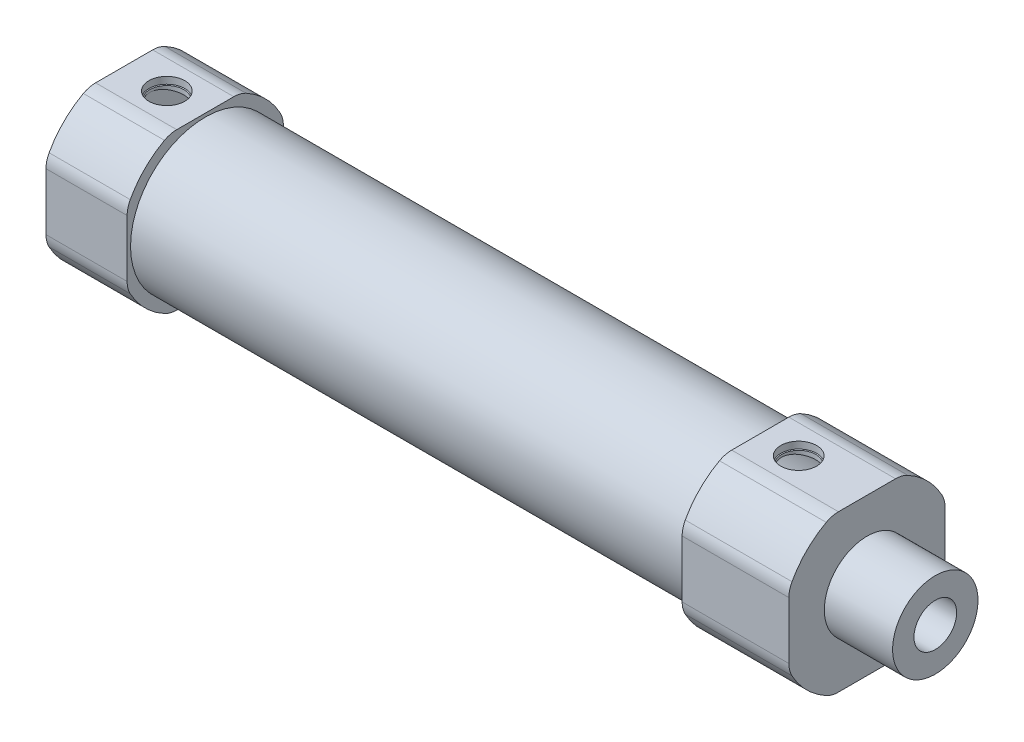
SolidWorks part; units mm, degrees
material "6061-T6 (SS)"
ref_plane "前视基准面" through (0, 0, 0) normal (0, 0, 1) x (1, 0, 0)
ref_plane "上视基准面" through (0, 0, 0) normal (0, 1, 0) x (1, 0, 0)
ref_plane "右视基准面" through (0, 0, 0) normal (1, 0, 0) x (0, 0, -1)
sketch "主筒" plane through (0, 0, 0) normal (1, 0, 0) x (0, 0, -1)
  circle A0 centre (0, 0) radius 8.75
  dimension "D1" = 17.5
extrude "主缸筒" add sketch "主筒" along normal blind 87
sketch "前头1" plane through (87, 0, 0) normal (1, 0, 0) x (0, 0, -1)
  line L1 (-9.15, 9.15) -> (9.15, 9.15)
  line L2 (-9.15, 9.15) -> (-9.15, -9.15)
  line L3 (-9.15, -9.15) -> (9.15, -9.15)
  line L4 (9.15, 9.15) -> (9.15, -9.15)
  line L5 (-9.15, 9.15) -> (9.15, -9.15) construction
  line L6 (-9.15, -9.15) -> (9.15, 9.15) construction
  circle A0 centre (0, 0) radius 10
  point P0 (0, 0)
  circle M3 centre (0, 0) radius 8.75
  dimension "D2" = 20
  dimension "D1" = 18.3
extrude "前头" add sketch "前头1" against normal blind 12.5 contours L2 A0 L3 M3
sketch "后头1" plane through (0, 0, 0) normal (-1, 0, 0) x (0, 0, 1)
  line L1 (-9.15, 9.15) -> (9.15, 9.15)
  line L2 (-9.15, 9.15) -> (-9.15, -9.15)
  line L3 (-9.15, -9.15) -> (9.15, -9.15)
  line L4 (9.15, 9.15) -> (9.15, -9.15)
  line L5 (-9.15, 9.15) -> (9.15, -9.15) construction
  line L6 (-9.15, -9.15) -> (9.15, 9.15) construction
  circle A0 centre (0, 0) radius 10
  point P0 (0, 0)
  circle M9 centre (0, 0) radius 8.75
  dimension "D2" = 20
  dimension "D1" = 18.3
extrude "后头" add sketch "后头1" against normal blind 9.5 contours L4 A0 L1 L2 L3 M9
sketch "气管接头1" plane through (0, 9.15, 0) normal (0, 1, 0) x (1, 0, 0)
  line L0 (0, 0) -> (87, 0) construction
  line L1 (87, -4.0345) -> (87, 4.0345) construction
  line L2 (0, 4.0345) -> (0, -4.0345) construction
  circle A0 centre (5, 0) radius 2
  circle A1 centre (79, 0) radius 2
  dimension "D1" = 5
  dimension "D3" = 4
  dimension "D2" = 8
extrude "气管接头" cut sketch "气管接头1" against normal blind 10
hole_wizard "外孔" positions "3D草图1" profile "草图5" tap size "M5" standard "GB"
sketch3d "3D草图1"
  point P0 (5, 9.15, 0)
  point P3 (79, 9.15, 0)
sketch "草图5" plane through (5, 9.15, 0) normal (1, 0, 0) x (0, 0, 1)
  line L0 (0, 0) -> (0, 2.0618)
  line L1 (0, 2.0618) -> (2.1, 0.8)
  line L2 (2.1, 0.8) -> (2.1, 0)
  line L5 (2.1, 0) -> (0, 0)
  line L10 (0, 2.0618) -> (-2.1, 0.8) construction
  line L11 (0, -6.35) -> (0, 107.95) construction
  dimension "螺纹孔钻头直径" = 4.2
  dimension "螺纹孔钻头深度" = 0.8
  dimension "导头角度" = 118
cosmetic thread "孔螺蚊线1" parameters "D1"=0.8, "D2"=5
cosmetic thread "孔螺蚊线3" parameters "D1"=0.8, "D2"=5
sketch "内腔1" plane through (87, 0, 0) normal (1, 0, 0) x (0, 0, -1)
  circle A0 centre (0, 0) radius 8
  dimension "D1" = 16
extrude "切除-拉伸3" cut sketch "内腔1" against normal offset from surface (81 mm away) 3 from offset 3 up to face at (0, 0, 0) offset against normal yes
sketch "气缸头1" plane through (87, 0, 0) normal (1, 0, 0) x (0, 0, -1)
  circle A0 centre (0, 0) radius 5
  dimension "D1" = 10
extrude "气缸头" add sketch "气缸头1" along normal blind 8
cosmetic thread "装饰螺纹线1" parameters "D1"=5, "D2"=6.647
sketch "内芯1" plane through (95, 0, 0) normal (1, 0, 0) x (0, 0, -1)
  circle A0 centre (0, 0) radius 2.5
  dimension "D1" = 5
extrude "内芯" cut sketch "内芯1" against normal up to next
fillet "圆角2" radius 3 8 edges at (4.75, -4.0345, 9.15) (4.75, 4.0345, 9.15) (4.75, 4.0345, -9.15) (4.75, -4.0345, -9.15) (4.75, -9.15, -4.0345) (4.75, -9.15, 4.0345) (4.75, 9.15, 4.0345) (4.75, 9.15, -4.0345)
fillet "圆角3" radius 3 8 edges at (80.75, -4.0345, -9.15) (80.75, 4.0345, -9.15) (80.75, 9.15, -4.0345) (80.75, 9.15, 4.0345) (80.75, 4.0345, 9.15) (80.75, -4.0345, 9.15) (80.75, -9.15, 4.0345) (80.75, -9.15, -4.0345)
equation "\"行程l\"= 50"
equation "\"D1@主缸筒\"=\"行程l\"+47"
equation "\"行程2\"= 200"
